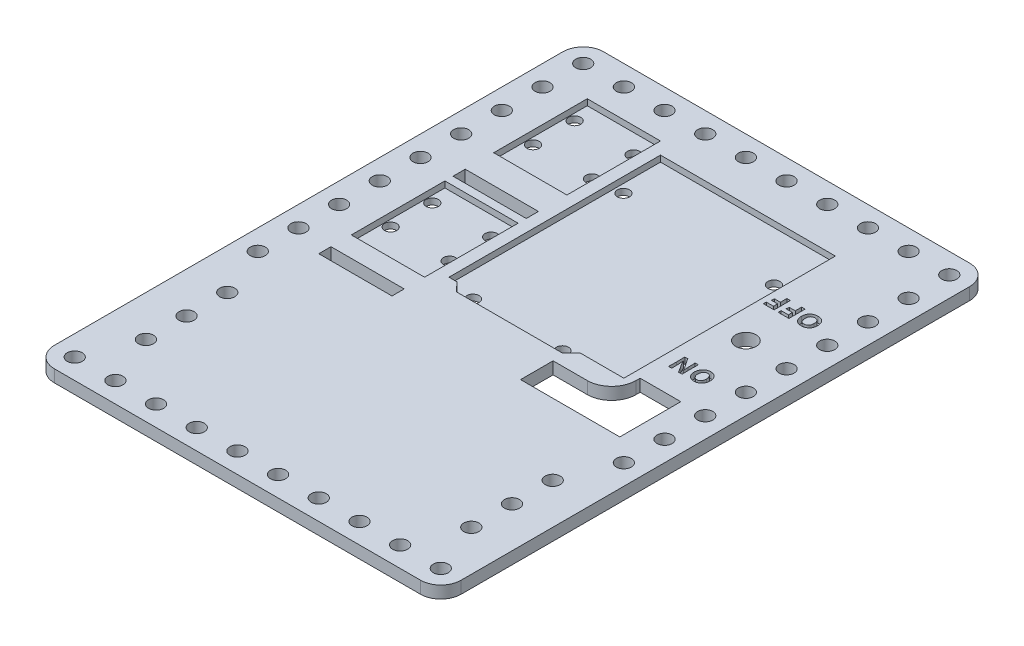
SolidWorks part; units mm, degrees
material "Copper"
ref_plane "Front Plane" through (0, 0, 0) normal (0, 0, 1) x (1, 0, 0)
ref_plane "Top Plane" through (0, 0, 0) normal (0, 1, 0) x (1, 0, 0)
ref_plane "Right Plane" through (0, 0, 0) normal (1, 0, 0) x (0, 0, -1)
sketch "Sketch1" plane through (0, 0, 0) normal (0, 1, 0) x (1, 0, 0)
  line L1 (6.35, 0) -> (120.65, 0)
  line L2 (0, 6.35) -> (0, 165.1)
  line L3 (6.35, 171.45) -> (120.65, 171.45)
  line L4 (127, 6.35) -> (127, 165.1)
  arc A0 (6.35, 0) -> (0, 6.35) centre (6.35, 6.35) cw
  arc A1 (120.65, 0) -> (127, 6.35) centre (120.65, 6.35) ccw
  arc A2 (120.65, 171.45) -> (127, 165.1) centre (120.65, 165.1) cw
  arc A3 (0, 165.1) -> (6.35, 171.45) centre (6.35, 165.1) cw
  point P7 (0, 0)
  point P10 (127, 0)
  point P13 (127, 171.45)
  point P16 (0, 171.45)
  dimension "D3" = 6.35
  dimension "D1" = 127
  dimension "D2" = 171.45
extrude "Plate Extrude" add sketch "Sketch1" along normal blind 3.81
sketch "Sketch2" plane through (0, 3.81, 0) normal (0, 1, 0) x (1, 0, 0)
  line L0 (120.65, 171.45) -> (6.35, 171.45) construction
  line L1 (0, 165.1) -> (0, 6.35) construction
  line L2 (6.35, 0) -> (120.65, 0) construction
  line L3 (63.5, 171.45) -> (63.5, 0) construction
  circle A0 centre (6.35, 165.1) radius 2.3495
  circle A1 centre (19.05, 165.1) radius 2.3495
  circle A2 centre (31.75, 165.1) radius 2.3495
  circle A3 centre (44.45, 165.1) radius 2.3495
  circle A4 centre (57.15, 165.1) radius 2.3495
  circle A5 centre (69.85, 165.1) radius 2.3495
  circle A6 centre (82.55, 165.1) radius 2.3495
  circle A7 centre (95.25, 165.1) radius 2.3495
  circle A8 centre (107.95, 165.1) radius 2.3495
  circle A9 centre (120.65, 165.1) radius 2.3495
  circle A10 centre (6.35, 152.4) radius 2.3495
  circle A11 centre (120.65, 152.4) radius 2.3495
  circle A12 centre (6.35, 139.7) radius 2.3495
  circle A13 centre (120.65, 139.7) radius 2.3495
  circle A14 centre (6.35, 127) radius 2.3495
  circle A15 centre (120.65, 127) radius 2.3495
  circle A16 centre (6.35, 114.3) radius 2.3495
  circle A17 centre (120.65, 114.3) radius 2.3495
  circle A18 centre (6.35, 101.6) radius 2.3495
  circle A19 centre (120.65, 101.6) radius 2.3495
  circle A20 centre (6.35, 88.9) radius 2.3495
  circle A21 centre (120.65, 88.9) radius 2.3495
  circle A22 centre (6.35, 76.2) radius 2.3495
  circle A23 centre (120.65, 76.2) radius 2.3495
  circle A24 centre (6.35, 63.5) radius 2.3495
  circle A25 centre (120.65, 63.5) radius 2.3495
  circle A26 centre (6.35, 6.35) radius 2.3495
  circle A27 centre (19.05, 6.35) radius 2.3495
  circle A28 centre (31.75, 6.35) radius 2.3495
  circle A29 centre (44.45, 6.35) radius 2.3495
  circle A30 centre (57.15, 6.35) radius 2.3495
  circle A31 centre (69.85, 6.35) radius 2.3495
  circle A32 centre (82.55, 6.35) radius 2.3495
  circle A33 centre (95.25, 6.35) radius 2.3495
  circle A34 centre (107.95, 6.35) radius 2.3495
  circle A35 centre (120.65, 6.35) radius 2.3495
  circle A36 centre (12.7, 22.225) radius 2.3495
  circle A37 centre (12.7, 34.925) radius 2.3495
  circle A38 centre (12.7, 47.625) radius 2.3495
  circle A39 centre (114.3, 47.625) radius 2.3495
  circle A40 centre (114.3, 34.925) radius 2.3495
  circle A41 centre (114.3, 22.225) radius 2.3495
  dimension "D1" = 4.699
  dimension "D2" = 6.35
  dimension "D6" = 4.699
  dimension "D7" = 6.35
  dimension "D8" = 6.35
  dimension "D10" = 4.699
  dimension "D11" = 12.7
  dimension "D12" = 22.225
  dimension "D3" = 6.35
  dimension "D4" = 10
  dimension "D5" = 9
  dimension "D9" = 10
  dimension "D13" = 3
extrude "Outer Hole Cut" cut sketch "Sketch2" against normal through all
sketch "Sketch3" plane through (0, 3.81, 0) normal (0, 1, 0) x (1, 0, 0)
  line L0 (81.28, 83.566) -> (84.074, 86.36)
  line L1 (43.18, 152.4) -> (97.79, 152.4)
  line L2 (43.18, 152.4) -> (43.18, 86.36)
  line L3 (43.18, 86.36) -> (97.79, 86.36)
  line L4 (97.79, 152.4) -> (97.79, 86.36)
  line L5 (81.28, 83.566) -> (48.26, 83.566)
  line L6 (48.26, 83.566) -> (45.72, 86.36)
  line L7 (127, 6.35) -> (127, 165.1) construction
  line L8 (120.65, 171.45) -> (6.35, 171.45) construction
  circle A0 centre (78.867, 86.106) radius 1.905
  circle A1 centre (50.927, 86.106) radius 1.905
  circle A2 centre (94.107, 136.906) radius 1.905
  circle A3 centre (45.847, 138.176) radius 1.905
  dimension "D1" = 3.81
  dimension "D9" = 52.07
  dimension "D2" = 54.61
  dimension "D3" = 66.04
  dimension "D4" = 40.894
  dimension "D5" = 38.1
  dimension "D6" = 5.08
  dimension "D7" = 27.94
  dimension "D8" = 7.747
  dimension "D10" = 50.8
  dimension "D11" = 15.24
  dimension "D12" = 5.08
  dimension "D13" = 2.54
  dimension "D14" = 2.794
  dimension "D15" = 2.54
  dimension "D16" = 29.21
  dimension "D17" = 19.05
extrude "Arduino Shape Cut" cut sketch "Sketch3" against normal blind 1.905 contours A1 L3 A0 L4 L1 L2 A3 A2 | A1 L3 L6 L5 L0 A0
sketch "Sketch4" plane through (0, 3.81, 0) normal (0, 1, 0) x (1, 0, 0)
  line L0 (43.18, 152.4) -> (43.18, 86.36) construction
  line L1 (16.51, 127) -> (39.37, 127)
  line L2 (16.51, 127) -> (16.51, 156.21)
  line L3 (16.51, 156.21) -> (39.37, 156.21)
  line L4 (39.37, 127) -> (39.37, 156.21)
  line L5 (43.18, 152.4) -> (97.79, 152.4) construction
  line L6 (16.51, 82.55) -> (39.37, 82.55)
  line L7 (16.51, 82.55) -> (16.51, 111.76)
  line L8 (39.37, 82.55) -> (39.37, 111.76)
  line L9 (16.51, 111.76) -> (39.37, 111.76)
  circle A0 centre (18.6057, 137.1834) radius 1.905
  circle A1 centre (18.6057, 150.1829) radius 1.905
  circle A2 centre (37.005, 150.1829) radius 1.905
  circle A3 centre (37.005, 137.1834) radius 1.905
  circle A4 centre (18.6057, 92.7334) radius 1.905
  circle A5 centre (18.6057, 105.7329) radius 1.905
  circle A6 centre (37.005, 105.7329) radius 1.905
  circle A7 centre (37.005, 92.7334) radius 1.905
  dimension "D1" = 3.81
  dimension "D9" = 18.3993
  dimension "D2" = 22.86
  dimension "D3" = 29.21
  dimension "D4" = 10.1834
  dimension "D5" = 2.365
  dimension "D6" = 3.81
  dimension "D7" = 12.9995
  dimension "D8" = 3.81
  dimension "D10" = 2
extrude "HG7881 Shape Cut" cut sketch "Sketch4" against normal blind 1.905 contours L1 L4 L3 L2 A3 A2 A1 A0 | L9 L7 L6 L8 A7 A6 A5 A4
sketch "Sketch5" plane through (0, 3.81, 0) normal (0, 1, 0) x (1, 0, 0)
  circle A0 centre (94.107, 136.906) radius 1.905 construction
  circle A1 centre (78.867, 86.106) radius 1.905 construction
  circle A2 centre (50.927, 86.106) radius 1.905 construction
  circle A3 centre (45.847, 138.176) radius 1.905 construction
  circle A4 centre (18.6057, 150.1829) radius 1.905 construction
  circle A5 centre (37.005, 150.1829) radius 1.905 construction
  circle A6 centre (37.005, 137.1834) radius 1.905 construction
  circle A7 centre (18.6057, 137.1834) radius 1.905 construction
  circle A8 centre (18.6057, 105.7329) radius 1.905 construction
  circle A9 centre (18.6057, 92.7334) radius 1.905 construction
  circle A10 centre (37.005, 92.7334) radius 1.905 construction
  circle A11 centre (37.005, 105.7329) radius 1.905 construction
  circle A12 centre (94.107, 136.906) radius 1.905
  circle A13 centre (78.867, 86.106) radius 1.905
  circle A14 centre (50.927, 86.106) radius 1.905
  circle A15 centre (45.847, 138.176) radius 1.905
  circle A16 centre (18.6057, 150.1829) radius 1.905
  circle A17 centre (37.005, 150.1829) radius 1.905
  circle A18 centre (37.005, 137.1834) radius 1.905
  circle A19 centre (18.6057, 137.1834) radius 1.905
  circle A20 centre (18.6057, 105.7329) radius 1.905
  circle A21 centre (18.6057, 92.7334) radius 1.905
  circle A22 centre (37.005, 92.7334) radius 1.905
  circle A23 centre (37.005, 105.7329) radius 1.905
extrude "Arduino and HG7881 Hole Cut" cut sketch "Sketch5" against normal through all
sketch "Sketch6" plane through (0, 3.81, 0) normal (0, 1, 0) x (1, 0, 0)
  line L0 (97.79, 133.35) -> (115.57, 133.35) construction
  line L1 (97.79, 152.4) -> (97.79, 86.36) construction
  line L2 (120.65, 171.45) -> (6.35, 171.45) construction
  line L3 (106.68, 101.6) -> (106.68, 133.35) construction
  line L4 (97.79, 101.6) -> (115.57, 101.6) construction
  circle A0 centre (106.68, 115.57) radius 3.175
  text T0 "OFF" font "Dubai" height 5.08
  text T1 "ON" font "Candara" height 5.08
  dimension "D4" = 6.35
  dimension "D1" = 17.78
  dimension "D2" = 31.75
  dimension "D3" = 38.1
  dimension "D5" = 13.97
extrude "On-Off Text Cut" cut sketch "Sketch6" against normal blind 1.905
sketch "Sketch8" plane through (0, 1.905, 0) normal (0, 1, 0) x (1, 0, 0)
  circle A0 centre (106.68, 115.57) radius 3.175 construction
  circle A1 centre (106.68, 115.57) radius 3.175
extrude "Switch Hole Cut" cut sketch "Sketch8" against normal through all
sketch "Sketch9" plane through (0, 3.81, 0) normal (0, 1, 0) x (1, 0, 0)
  line L0 (113.03, 69.85) -> (82.0443, 69.85)
  line L1 (82.0443, 69.85) -> (82.0443, 80.01)
  line L2 (113.03, 69.85) -> (113.03, 88.9)
  line L3 (113.03, 88.9) -> (100.33, 88.9)
  line L4 (100.33, 88.9) -> (100.33, 87.63)
  line L5 (92.71, 80.01) -> (82.0443, 80.01)
  line L6 (97.79, 152.4) -> (97.79, 86.36) construction
  line L7 (84.074, 86.36) -> (97.79, 86.36) construction
  arc A0 (100.33, 87.63) -> (92.71, 80.01) centre (92.71, 87.63) cw
  dimension "D7" = 7.62
  dimension "D1" = 12.7
  dimension "D2" = 2.54
  dimension "D3" = 19.05
  dimension "D4" = 10.16
  dimension "D5" = 30.9857
  dimension "D6" = 2.54
extrude "Battery Wire Cut" cut sketch "Sketch9" against normal through all
sketch "Sketch10" plane through (0, 3.81, 0) normal (0, 1, 0) x (1, 0, 0)
  line L0 (16.51, 82.55) -> (16.51, 111.76) construction
  line L1 (39.37, 114.3) -> (16.51, 114.3)
  line L2 (39.37, 114.3) -> (39.37, 118.11)
  line L3 (39.37, 118.11) -> (16.51, 118.11)
  line L4 (16.51, 114.3) -> (16.51, 118.11)
  line L5 (39.37, 82.55) -> (39.37, 111.76) construction
  line L6 (16.51, 127) -> (39.37, 127) construction
  line L7 (39.37, 72.39) -> (16.51, 72.39)
  line L8 (39.37, 72.39) -> (39.37, 76.2)
  line L9 (39.37, 76.2) -> (16.51, 76.2)
  line L10 (16.51, 72.39) -> (16.51, 76.2)
  line L11 (16.51, 82.55) -> (39.37, 82.55) construction
  dimension "D1" = 3.81
  dimension "D2" = 12.7
  dimension "D3" = 3.81
  dimension "D4" = 10.16
extrude "Motor Wire Cut" cut sketch "Sketch10" against normal through all
